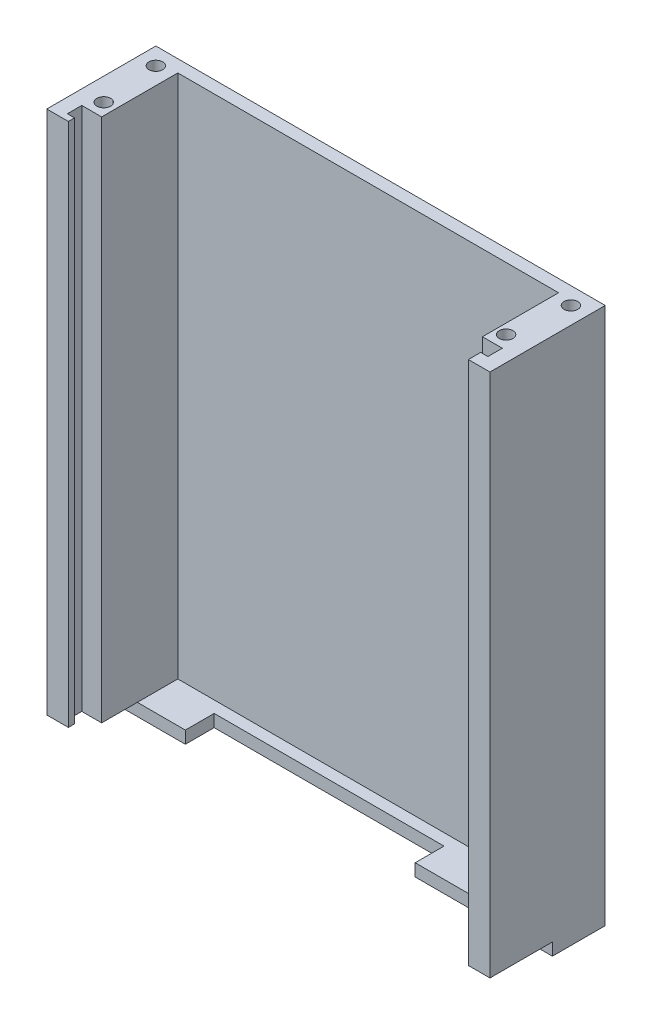
SolidWorks part; units mm, degrees
ref_plane "Alzado" through (0, 0, 0) normal (0, 0, 1) x (1, 0, 0)
ref_plane "Planta" through (0, 0, 0) normal (0, 1, 0) x (1, 0, 0)
ref_plane "Vista lateral" through (0, 0, 0) normal (1, 0, 0) x (0, 0, -1)
sketch "Croquis1" plane through (0, 0, 0) normal (0, 0, 1) x (1, 0, 0)
  line L1 (-90.9615, 34.8077) -> (-25.4615, 34.8077)
  line L2 (-90.9615, 34.8077) -> (-90.9615, -41.6923)
  line L3 (-90.9615, -41.6923) -> (-25.4615, -41.6923)
  line L4 (-25.4615, 34.8077) -> (-25.4615, -41.6923)
  dimension "D1" = 65.5
  dimension "D2" = 76.5
extrude "Saliente-Extruir1" add sketch "Croquis1" along normal blind 1.8
sketch "Croquis2" plane through (0, 0, 1.8) normal (0, 0, 1) x (1, 0, 0)
  line L0 (-90.9615, -41.6923) -> (-25.4615, -41.6923) construction
  line L1 (-90.9615, 34.8077) -> (-85.9615, 34.8077)
  line L2 (-90.9615, 34.8077) -> (-90.9615, -41.6923)
  line L3 (-90.9615, -41.6923) -> (-85.9615, -41.6923)
  line L4 (-85.9615, 34.8077) -> (-85.9615, -41.6923)
  line L6 (-25.4615, 34.8077) -> (-30.4615, 34.8077)
  line L7 (-25.4615, 34.8077) -> (-25.4615, -41.6923)
  line L8 (-25.4615, -41.6923) -> (-30.4615, -41.6923)
  line L9 (-30.4615, 34.8077) -> (-30.4615, -41.6923)
  dimension "D1" = 5
  dimension "D2" = 5
extrude "Saliente-Extruir2" add sketch "Croquis2" along normal blind 15
sketch "Croquis3" plane through (0, -41.6923, 0) normal (0, -1, 0) x (1, 0, 0)
  line L1 (-90.9615, 16.8) -> (-85.9615, 16.8) construction
  line L3 (-89.1115, 15.9) -> (-87.8115, 15.9)
  line L6 (-88.4615, 15.9) -> (-88.4615, 15) construction
  line L7 (-90.9615, 15) -> (-88.8615, 15) construction
  line L8 (-90.9615, 16.8) -> (-90.9615, 0) construction
  line L9 (-85.9615, 16.8) -> (-85.9615, 1.8) construction
  line L13 (-85.9615, 15) -> (-85.9615, 12.9)
  line L14 (-58.2115, 1.8) -> (-58.2115, 0) construction
  line L15 (-85.9615, 1.8) -> (-30.4615, 1.8) construction
  line L16 (-90.9615, 0) -> (-25.4615, 0) construction
  line L17 (-25.4615, 15) -> (-27.5615, 15) construction
  line L18 (-27.9615, 15.9) -> (-27.9615, 15) construction
  line L19 (-30.4615, 15) -> (-30.4615, 12.9)
  line L20 (-27.5615, 12.9) -> (-30.4615, 12.9)
  line L21 (-27.5615, 15) -> (-27.5615, 12.9)
  line L28 (-28.6115, 15.9) -> (-28.6115, 15)
  line L29 (-28.6115, 16.8) -> (-30.4615, 16.8)
  line L30 (-30.4615, 16.8) -> (-30.4615, 15)
  line L31 (-28.6115, 15) -> (-27.5615, 15)
  line L33 (-89.1115, 16.8) -> (-85.9615, 16.8)
  line L34 (-88.8615, 15) -> (-88.4615, 15)
  line L35 (-87.8115, 15.9) -> (-87.8115, 15)
  line L37 (-87.8115, 15) -> (-88.4615, 15)
  line L38 (-88.8615, 12.9) -> (-85.9615, 12.9)
  line L39 (-88.8615, 12.9) -> (-88.8615, 15)
  line L40 (-85.9615, 16.8) -> (-85.9615, 15)
  line L41 (-89.1115, 16.8) -> (-90.9615, 16.8)
  line L42 (-90.9615, 16.8) -> (-90.9615, 15.9)
  line L43 (-90.9615, 15.9) -> (-89.1115, 15.9)
  line L44 (-28.6115, 15.9) -> (-28.6115, 16.8)
  dimension "D1" = 1.3
  dimension "D2" = 0.9
  dimension "D3" = 2.1
  dimension "D4" = 0.9
  dimension "D5" = 2.1
extrude "Cortar-Extruir1" cut sketch "Croquis3" against normal up to vertex (76.5 mm away)
sketch "Croquis6" plane through (0, -41.6923, 0) normal (0, -1, 0) x (1, 0, 0)
  line L0 (-88.8615, 12.9) -> (-85.9615, 12.9) construction
  line L1 (-85.9615, 12.9) -> (-85.9615, 1.8) construction
  line L3 (-85.9615, 7.7) -> (-78.9615, 7.7)
  line L7 (-30.4615, 12.9) -> (-30.4615, 1.8) construction
  line L8 (-30.4615, 7.7) -> (-45.4615, 7.7)
  line L12 (-85.9615, 7.7) -> (-90.9615, 7.7)
  line L13 (-90.9615, 15.9) -> (-90.9615, 0) construction
  line L14 (-90.9615, 7.7) -> (-90.9615, 0)
  line L15 (-90.9615, 0) -> (-25.4615, 0)
  line L16 (-25.4615, 0) -> (-25.4615, 7.7)
  line L17 (-25.4615, 16.8) -> (-25.4615, 0) construction
  line L18 (-25.4615, 7.7) -> (-30.4615, 7.7)
  line L20 (-30.4615, 12.9) -> (-27.5615, 12.9) construction
  line L22 (-78.9615, 7.7) -> (-78.9615, 3.5)
  line L23 (-45.4615, 7.7) -> (-45.4615, 3.5)
  line L24 (-45.4615, 3.5) -> (-78.9615, 3.5)
  point P27 (-29.0115, 12.9)
  dimension "D1" = 5.2
  dimension "D2" = 7
  dimension "D3" = 15
  dimension "D4" = 5.2
  dimension "D5" = 3.5
extrude "Saliente-Extruir4" add sketch "Croquis6" along normal blind 1.8
sketch "Croquis7" plane through (0, 0, 0) normal (0, 0, -1) x (-1, 0, 0)
  line L0 (58.2115, -43.4923) -> (58.2115, 34.8077) construction
  line L1 (90.9615, -43.4923) -> (25.4615, -43.4923) construction
  line L2 (25.4615, 34.8077) -> (90.9615, 34.8077) construction
  line L4 (51.2865, -15.8423) -> (65.1365, -15.8423)
  line L5 (51.2865, -15.8423) -> (51.2865, 7.1577)
  line L6 (51.2865, 7.1577) -> (65.1365, 7.1577)
  line L7 (65.1365, -15.8423) -> (65.1365, 7.1577)
  line L8 (51.2865, -15.8423) -> (65.1365, 7.1577) construction
  line L9 (51.2865, 7.1577) -> (65.1365, -15.8423) construction
  point P6 (58.2115, -4.3423)
  dimension "D1" = 13.85
  dimension "D2" = 23
extrude "Saliente-Extruir5" add sketch "Croquis7" along normal blind 3
sketch "Croquis9" plane through (0, -15.8423, 0) normal (0, -1, 0) x (1, 0, 0)
  line L0 (-51.2865, -3) -> (-54.2865, 0)
  line L1 (-51.2865, 0) -> (-65.1365, 0) construction
  line L2 (-54.2865, 0) -> (-51.2865, 0)
  line L3 (-51.2865, 0) -> (-51.2865, -3)
  line L4 (-65.1365, -3) -> (-62.1365, 0)
  line L5 (-62.1365, 0) -> (-65.1365, 0)
  line L6 (-65.1365, 0) -> (-65.1365, -3)
  dimension "D1" = 45
extrude "Cortar-Extruir5" cut sketch "Croquis9" against normal up to vertex (23 mm away)
sketch "Croquis10" plane through (0, -41.6923, 0) normal (0, -1, 0) x (1, 0, 0)
  line L0 (-87.6615, 10.9) -> (-87.6615, 12.9) construction
  line L2 (-29.0115, 12.9) -> (-29.0115, 10.9) construction
  line L3 (-30.4615, 12.9) -> (-27.5615, 12.9) construction
  line L4 (-88.8615, 12.9) -> (-85.9615, 12.9) construction
  circle A0 centre (-87.6615, 10.9) radius 1
  circle A1 centre (-29.0115, 10.9) radius 1
extrude "Cortar-Extruir6" cut sketch "Croquis10" against normal blind 8
sketch "Croquis11" plane through (0, 34.8077, 0) normal (0, 1, 0) x (1, 0, 0)
  line L0 (-29.0115, -12.9) -> (-29.0115, -10.9) construction
  line L1 (-30.4615, -12.9) -> (-27.5615, -12.9) construction
  line L2 (-87.6615, -10.9) -> (-87.6615, -12.9) construction
  line L4 (-88.8615, -12.9) -> (-85.9615, -12.9) construction
  circle A0 centre (-29.0115, -10.9) radius 1
  circle A1 centre (-87.6615, -10.9) radius 1
extrude "Cortar-Extruir7" cut sketch "Croquis11" against normal blind 8
sketch "Croquis12" plane through (0, 34.8077, 0) normal (0, 1, 0) x (1, 0, 0)
  line L0 (-25.4615, -16.8) -> (-25.4615, 0) construction
  line L1 (-25.4615, 0) -> (-90.9615, 0) construction
  line L2 (-90.9615, -15.9) -> (-90.9615, 0) construction
  circle A0 centre (-27.9615, -2.5) radius 1
  circle A1 centre (-88.4615, -2.5) radius 1
  dimension "D1" = 2.5
  dimension "D2" = 2.5
  dimension "D3" = 2.5
  dimension "D4" = 2.5
extrude "Cortar-Extruir8" cut sketch "Croquis12" against normal blind 8
